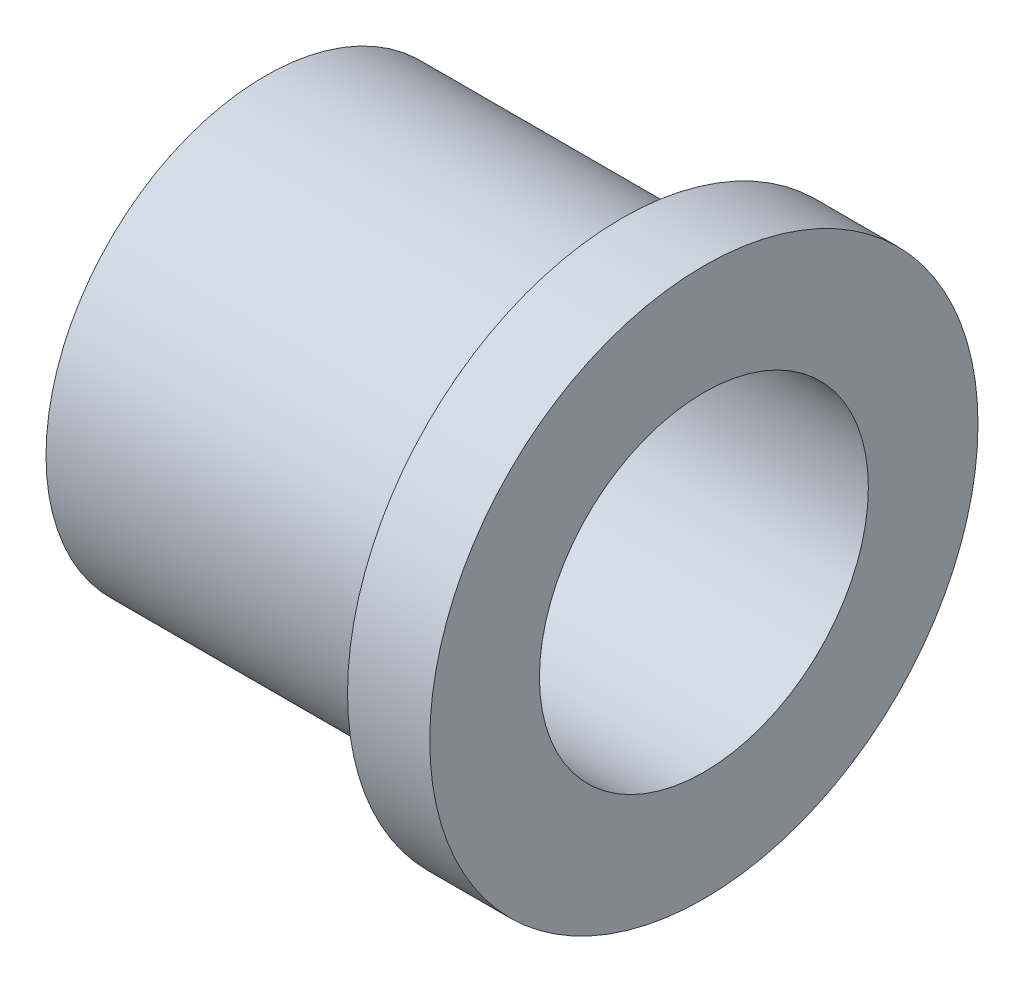
SolidWorks part; units mm, degrees
material "Aluminum Bronze"
ref_plane "Front Plane" through (0, 0, 0) normal (0, 0, 1) x (1, 0, 0)
ref_plane "Top Plane" through (0, 0, 0) normal (0, 1, 0) x (1, 0, 0)
ref_plane "Right Plane" through (0, 0, 0) normal (1, 0, 0) x (0, 0, -1)
sketch "Sketch1" plane through (0, 0, 0) normal (0, 0, 1) x (1, 0, 0)
  line L0 (-25.4, 12.7) -> (-4.7625, 12.7)
  line L1 (-4.7625, 12.7) -> (-4.7625, 15.875)
  line L2 (-4.7625, 15.875) -> (0, 15.875)
  line L3 (0, 15.875) -> (0, 9.525)
  line L4 (0, 9.525) -> (-25.4, 9.525)
  line L5 (-25.4, 9.525) -> (-25.4, 12.7)
  line L6 (0, 0) -> (31.0462, 0) construction
  dimension "D1" = 9.525
  dimension "D2" = 12.7
  dimension "D3" = 4.7625
  dimension "D4" = 25.4
  dimension "D5" = 15.875
revolve "Revolve1" add sketch "Sketch1" angle 360 about L6
